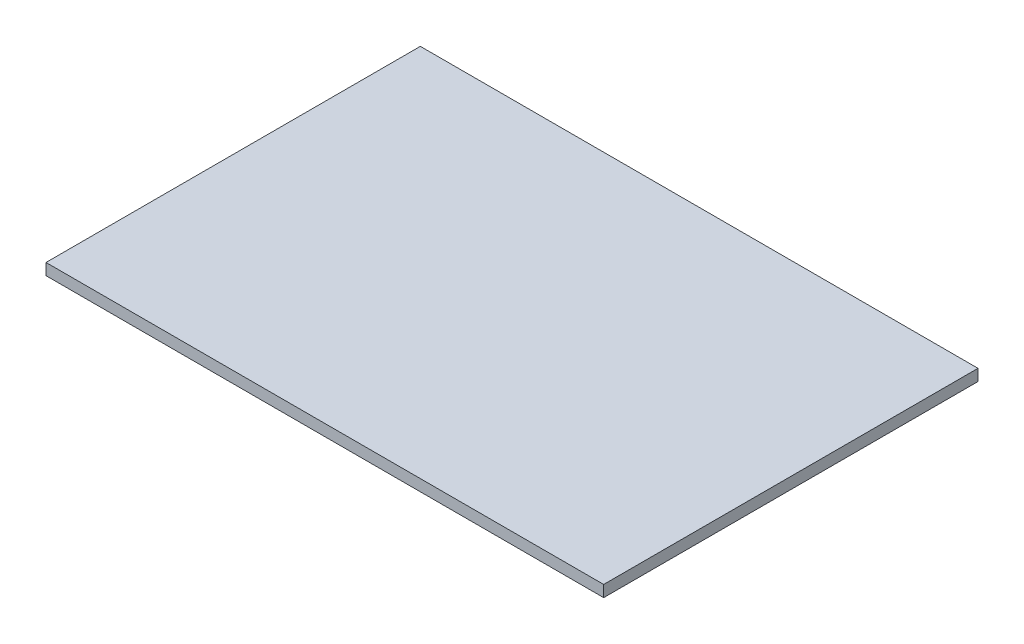
SolidWorks part; units mm, degrees
ref_plane "Front Plane" through (0, 0, 0) normal (0, 0, 1) x (1, 0, 0)
ref_plane "Top Plane" through (0, 0, 0) normal (0, 1, 0) x (1, 0, 0)
ref_plane "Right Plane" through (0, 0, 0) normal (1, 0, 0) x (0, 0, -1)
sketch "Sketch1" plane through (0, 0, 0) normal (0, 1, 0) x (1, 0, 0)
  line L1 (0, 0) -> (927.1, 0)
  line L2 (0, 0) -> (0, 622.3)
  line L3 (0, 622.3) -> (927.1, 622.3)
  line L4 (927.1, 0) -> (927.1, 622.3)
  dimension "D1" = 927.1
  dimension "D2" = 622.3
extrude "Boss-Extrude1" add sketch "Sketch1" along normal blind 19.05
